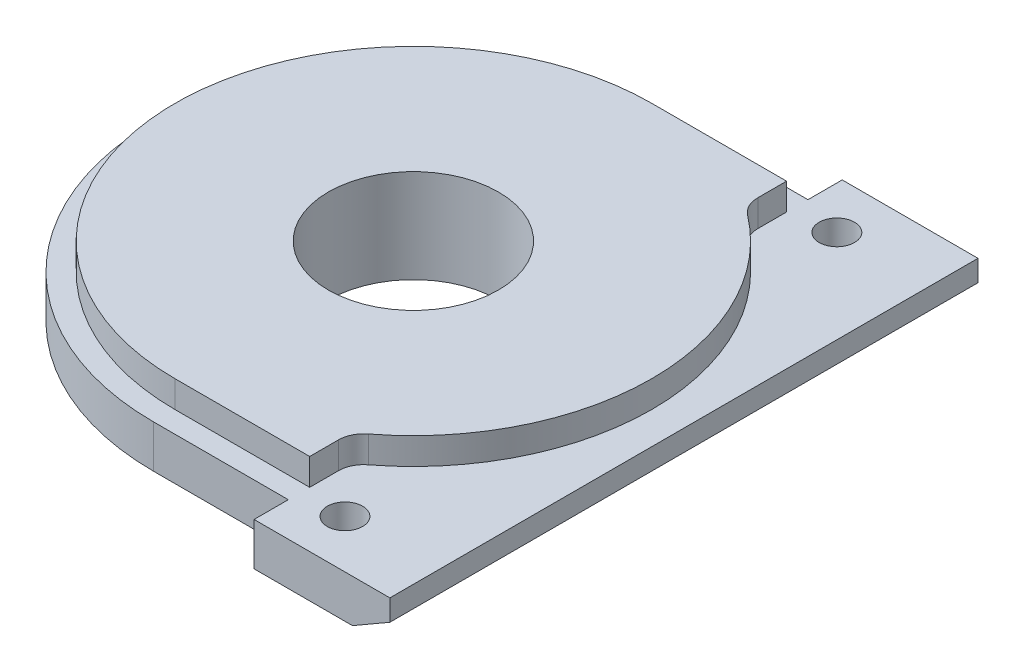
SolidWorks part; units mm, degrees
material "6061-T6 (SS)"
ref_plane "Front Plane" through (0, 0, 0) normal (0, 0, 1) x (1, 0, 0)
ref_plane "Top Plane" through (0, 0, 0) normal (0, 1, 0) x (1, 0, 0)
ref_plane "Right Plane" through (0, 0, 0) normal (1, 0, 0) x (0, 0, -1)
sketch "Sketch1" plane through (0, 0, 0) normal (0, 1, 0) x (1, 0, 0)
  line L0 (-13.2912, 20.8898) -> (-0.69, 20.8898)
  line L5 (-13.2912, -23.7056) -> (-0.69, -23.7056)
  line L7 (-0.69, -23.7056) -> (-0.69, -28.9079)
  line L8 (-0.69, -28.9079) -> (12.01, -28.9079)
  line L9 (-0.69, 20.8898) -> (-0.69, 26.0921)
  line L10 (12.01, -28.9079) -> (12.01, 26.0921)
  line L11 (12.01, 26.0921) -> (-0.69, 26.0921)
  arc A0 (-13.2912, 20.8898) -> (-13.2912, -23.7056) centre (-13.2912, -1.4079) ccw
extrude "Boss-Extrude1" add sketch "Sketch1" along normal blind 4
sketch "Sketch2" plane through (0, 4, 0) normal (0, 1, 0) x (1, 0, 0)
  line L4 (-13.2912, 20.8898) -> (-0.69, 20.8898)
  line L5 (-0.69, 20.8898) -> (-0.69, 16.9877)
  line L6 (-13.2912, -23.7056) -> (-0.69, -23.7056)
  line L7 (-0.69, -23.7056) -> (-0.69, -19.8035)
  arc A0 (-0.69, -19.8035) -> (-0.69, 16.9877) centre (-13.2912, -1.4079) ccw
  arc A1 (-13.2912, 20.8898) -> (-13.2912, -23.7056) centre (-13.2912, -1.4079) ccw
extrude "Boss-Extrude2" add sketch "Sketch2" along normal blind 2.5
sketch "Sketch3" plane through (0, 0, 0) normal (0, -1, 0) x (1, 0, 0)
  circle A0 centre (-13.2912, 1.4079) radius 7.95
  dimension "D1" = 15.9
extrude "Cut-Extrude1" cut sketch "Sketch3" against normal blind 9.25
sketch "Sketch4" plane through (0, 0, 0) normal (0, -1, 0) x (1, 0, 0)
  line L0 (3.31, -21.5921) -> (3.31, -26.0921) construction
  line L2 (12.01, -26.0921) -> (-0.69, -26.0921) construction
  line L3 (3.31, -26.0921) -> (-0.69, -26.0921) construction
  line L5 (3.31, 24.4079) -> (3.31, 28.9079) construction
  line L6 (-0.69, 28.9079) -> (12.01, 28.9079) construction
  line L7 (3.31, 28.9079) -> (-0.69, 28.9079) construction
  circle A0 centre (3.31, 24.4079) radius 1.65
  circle A1 centre (3.31, -21.5921) radius 1.65
  dimension "D1" = 4.5
  dimension "D2" = 3.3
  dimension "D4" = 3.3
  dimension "D3" = 4.5
extrude "Cut-Extrude2" cut sketch "Sketch4" against normal blind 9.25
sketch "Sketch5" plane through (0, 0, 0) normal (0, -1, 0) x (1, 0, 0)
  line L9 (-20.9172, 10.6082) -> (-24.2357, 16.3644)
  line L12 (-17.4459, 12.6124) -> (-20.7716, 18.3644)
  line L14 (-1.5104, 3.4121) -> (5.1338, 3.4079)
  line L17 (-1.5104, -0.5963) -> (5.1338, -0.5921)
  line L19 (-17.4459, -9.7966) -> (-20.7716, -15.5486)
  line L22 (-20.9172, -7.7924) -> (-24.2357, -13.5486)
  circle A2 centre (-13.2912, 1.4079) radius 11.95
  arc A3 (-1.5104, 3.4121) -> (-17.4459, 12.6124) centre (-13.2912, 1.4079) ccw
  circle A4 centre (-13.2912, 1.4079) radius 18.45
  circle A5 centre (-13.2912, 1.4079) radius 18.45
  circle A6 centre (-13.2912, 1.4079) radius 18.45
  circle A7 centre (-13.2912, 1.4079) radius 18.45
  arc A8 (-20.9172, 10.6082) -> (-20.9172, -7.7924) centre (-13.2912, 1.4079) ccw
  arc A9 (-17.4459, -9.7966) -> (-1.5104, -0.5963) centre (-13.2912, 1.4079) ccw
  point P14 (-13.2912, 1.4079)
  dimension "D1" = 4
  dimension "D2" = 10.5
  dimension "D3" = 3
extrude "Cut-Extrude3" cut sketch "Sketch5" against normal blind 3.25 contours A8 L9 A4 L22 | L14 A4 L12 A3 | A9 L19 A4 L17
fillet "Fillet1" radius 2.3813 12 edges at (5.0501, 1.625, 3.4079) (-1.5104, 1.625, 3.4121) (5.0501, 1.625, -0.5922) (-24.1939, 1.625, 16.2919) (-20.7297, 1.625, 18.2919) (-1.5104, 1.625, -0.5963) (-20.7297, 1.625, -15.4761) (-20.9172, 1.625, 10.6082) (-20.9172, 1.625, -7.7924) (-24.1939, 1.625, -13.4761) (-17.4459, 1.625, -9.7966) (-17.4459, 1.625, 12.6124)
chamfer "Chamfer1" distance 3.5 angle 30 1 edges at (12.01, 0, 1.4079)
sketch "Sketch10" plane through (0, 0, 0) normal (0, -1, 0) x (1, 0, 0)
  line L2 (-0.69, -22.8898) -> (-13.2912, -22.8898)
  line L3 (-13.2912, 25.7056) -> (-0.69, 25.7056)
  line L4 (-0.69, -20.8898) -> (-13.2912, -20.8898)
  line L5 (-13.2912, 23.7056) -> (-0.69, 23.7056)
  line L6 (-0.69, -20.8898) -> (-13.2912, -20.8898)
  line L7 (-13.2912, 23.7056) -> (-0.69, 23.7056)
  line L8 (-0.69, 25.7056) -> (-0.69, 23.7056)
  line L9 (-0.69, -20.8898) -> (-0.69, -22.8898)
  arc A1 (-13.2912, 25.7056) -> (-13.2912, -22.8898) centre (-13.2912, 1.4079) ccw
  arc A2 (-13.2912, 23.7056) -> (-13.2912, -20.8898) centre (-13.2912, 1.4079) ccw
  arc A3 (-13.2912, 23.7056) -> (-13.2912, -20.8898) centre (-13.2912, 1.4079) ccw
  dimension "D1" = 0
  dimension "D2" = 2
extrude "Boss-Extrude4" add sketch "Sketch10" against normal blind 4
sketch "Sketch11" plane through (0, 0, 0) normal (0, -1, 0) x (1, 0, 0)
  circle A1 centre (-13.2912, 1.4079) radius 11.95
extrude "Boss-Extrude5" add sketch "Sketch11" along normal blind 2.25
sketch "Sketch12" plane through (0, 0, 0) normal (0, 1, 0) x (1, 0, 0)
  circle A2 centre (-13.2912, -1.4079) radius 7.95
  circle A3 centre (-13.2912, -1.4079) radius 7.95
  dimension "D1" = 0
extrude "Cut-Extrude4" cut sketch "Sketch12" against normal blind 2.25
fillet "Fillet5" radius 2.38 2 edges at (-0.69, 5.25, -16.9877) (-0.69, 5.25, 19.8035)
